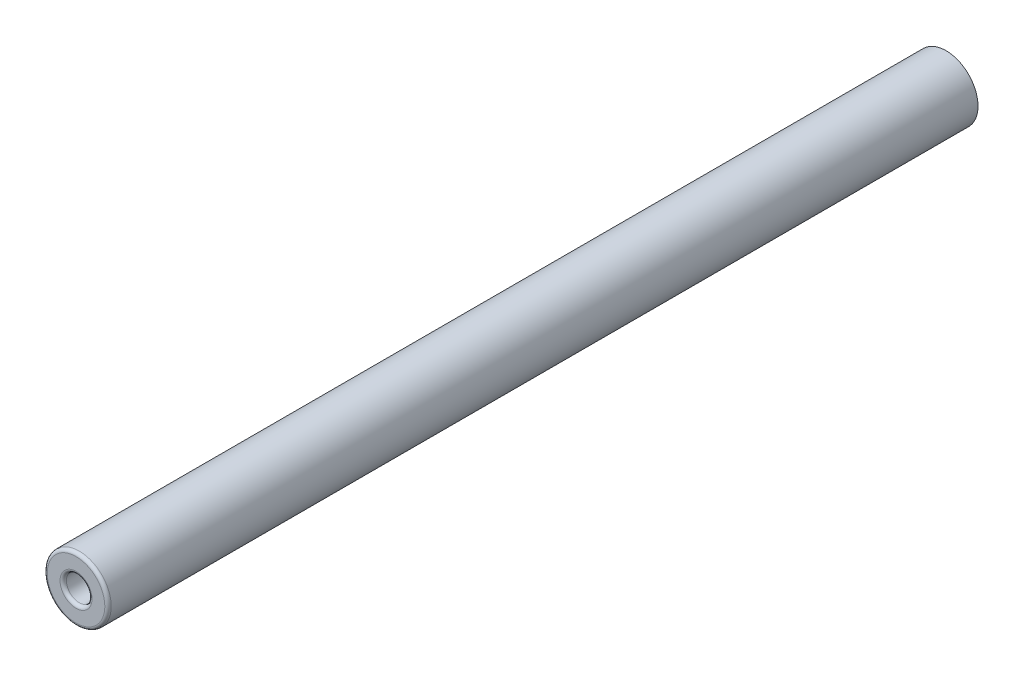
SolidWorks part; units mm, degrees
ref_plane "Front Plane" through (0, 0, 0) normal (0, 0, 1) x (1, 0, 0)
ref_plane "Top Plane" through (0, 0, 0) normal (0, 1, 0) x (1, 0, 0)
ref_plane "Right Plane" through (0, 0, 0) normal (1, 0, 0) x (0, 0, -1)
sketch "Sketch1" plane through (0, 0, 0) normal (0, 0, 1) x (1, 0, 0)
  circle A0 centre (0, 0) radius 7.5
  dimension "D1" = 15
extrude "Boss-Extrude1" add sketch "Sketch1" along normal blind 204
sketch "Sketch2" plane through (0, 0, 204) normal (0, 0, 1) x (1, 0, 0)
  circle A0 centre (0, 0) radius 3
  dimension "D1" = 6
extrude "Cut-Extrude1" cut sketch "Sketch2" against normal blind 30
fillet "Fillet1" radius 0.75 2 edges at (7.5, 0, 204) (3, 0, 204)
scale "Escala2" scale about centroid uniform scaling yes scale factor 0.5
